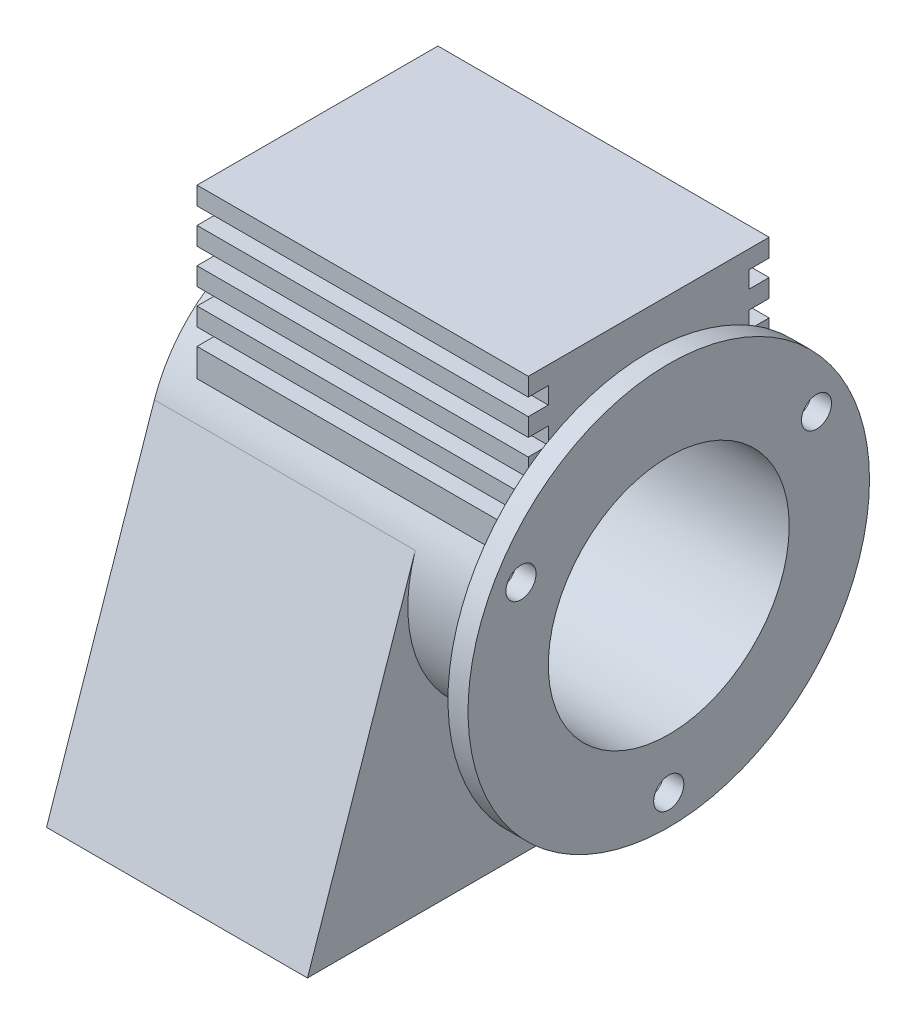
SolidWorks part; units mm, degrees
ref_plane "Front Plane" through (0, 0, 0) normal (0, 0, 1) x (1, 0, 0)
ref_plane "Top Plane" through (0, 0, 0) normal (0, 1, 0) x (1, 0, 0)
ref_plane "Right Plane" through (0, 0, 0) normal (1, 0, 0) x (0, 0, -1)
sketch "Sketch1" plane through (0, 0, 0) normal (1, 0, 0) x (0, 0, -1)
  circle A0 centre (0, 0) radius 50
  circle A1 centre (0, 0) radius 30
  dimension "D1" = 60
  dimension "D2" = 100
extrude "Boss-Extrude1" add sketch "Sketch1" along normal blind 5
sketch "Sketch2" plane through (0, 0, 0) normal (-1, 0, 0) x (0, 0, 1)
  circle A0 centre (0, 0) radius 30 construction
  circle A1 centre (0, 0) radius 30
  circle A2 centre (0, 0) radius 35
  dimension "D1" = 70
extrude "Boss-Extrude2" add sketch "Sketch2" along normal blind 82.5
ref_plane "Plane1" through (-90, 0, 0) normal (-1, 0, 0) x (0, 0, 1)
sketch "Sketch3" plane through (-90, 0, 0) normal (-1, 0, 0) x (0, 0, 1)
  line L0 (0, 0) -> (0, -67.5) construction
  line L1 (-60, -67.5) -> (60, -67.5)
  line L2 (-60, -67.5) -> (-33.1265, 11.2976)
  line L3 (60, -67.5) -> (33.1265, 11.2976)
  circle A0 centre (0, 0) radius 35 construction
  arc A1 (33.1265, 11.2976) -> (-33.1265, 11.2976) centre (0, 0) ccw
  dimension "D1" = 120
extrude "Boss-Extrude3" add sketch "Sketch3" against normal blind 65
sketch "Sketch4" plane through (5, 0, 0) normal (1, 0, 0) x (0, 0, -1)
  circle A0 centre (0, 0) radius 42.5 construction
  circle A1 centre (0, -42.5) radius 3.75
  circle A2 centre (-36.8061, 21.25) radius 3.75
  circle A3 centre (36.8061, 21.25) radius 3.75
  circle A4 centre (0, 0) radius 50 construction
  point P11 (0, 0)
  dimension "D1" = 85
  dimension "D2" = 7.5
  dimension "D3" = 3
extrude "Cut-Extrude2" cut sketch "Sketch4" against normal blind 5
sketch "Sketch6" plane through (0, 0, 0) normal (-1, 0, 0) x (0, 0, 1)
  line L0 (-25, 25) -> (-30, 25)
  line L1 (30, 59.8) -> (-30, 59.8)
  line L2 (-30, 59.8) -> (-30, 55.3)
  line L3 (-30, 55.3) -> (-25, 55.3)
  line L4 (-25, 55.3) -> (-25, 51.1)
  line L5 (-25, 51.1) -> (-30, 51.1)
  line L6 (-30, 51.1) -> (-30, 46.6)
  line L7 (-30, 46.6) -> (-25, 46.6)
  line L8 (-25, 46.6) -> (-25, 42.4)
  line L9 (-25, 42.4) -> (-30, 42.4)
  line L10 (-30, 42.4) -> (-30, 37.9)
  line L11 (-30, 37.9) -> (-25, 37.9)
  line L12 (-25, 37.9) -> (-25, 33.7)
  line L13 (-25, 33.7) -> (-30, 33.7)
  line L14 (-30, 33.7) -> (-30, 29.2)
  line L15 (-30, 29.2) -> (-25, 29.2)
  line L16 (-25, 29.2) -> (-25, 25)
  line L17 (-30, 25) -> (-30, 18.0278)
  line L18 (0, 0) -> (0, 59.8) construction
  line L19 (30, 25) -> (30, 18.0278)
  line L20 (25, 29.2) -> (25, 25)
  line L21 (30, 29.2) -> (25, 29.2)
  line L22 (30, 33.7) -> (30, 29.2)
  line L23 (25, 33.7) -> (30, 33.7)
  line L24 (25, 37.9) -> (25, 33.7)
  line L25 (30, 37.9) -> (25, 37.9)
  line L26 (30, 42.4) -> (30, 37.9)
  line L27 (25, 42.4) -> (30, 42.4)
  line L28 (25, 46.6) -> (25, 42.4)
  line L29 (30, 46.6) -> (25, 46.6)
  line L30 (30, 51.1) -> (30, 46.6)
  line L31 (25, 51.1) -> (30, 51.1)
  line L32 (25, 55.3) -> (25, 51.1)
  line L33 (30, 55.3) -> (25, 55.3)
  line L34 (30, 59.8) -> (30, 55.3)
  line L35 (25, 25) -> (30, 25)
  circle A0 centre (0, -42.5) radius 3.75 construction
  arc A1 (33.1265, 11.2976) -> (-33.1265, 11.2976) centre (0, 0) ccw construction
  arc A3 (30, 18.0278) -> (-30, 18.0278) centre (0, 0) ccw
  dimension "D1" = 25
  dimension "D2" = 30
  dimension "D3" = 5
  dimension "D4" = 4.2
  dimension "D5" = 8.7
extrude "Boss-Extrude4" add sketch "Sketch6" along normal blind 82.5
sketch "Sketch7" plane through (-25, 0, 0) normal (1, 0, 0) x (0, 0, -1)
  circle A0 centre (0, 0) radius 7.5
  dimension "D1" = 15
extrude "Cut-Extrude3" cut sketch "Sketch7" against normal through all
sketch "Sketch8" plane through (-25, 0, 0) normal (1, 0, 0) x (0, 0, -1)
  circle A0 centre (0, 0) radius 30 construction
  circle A1 centre (0, 0) radius 30
extrude "Cut-Extrude4" cut sketch "Sketch8" against normal blind 60
